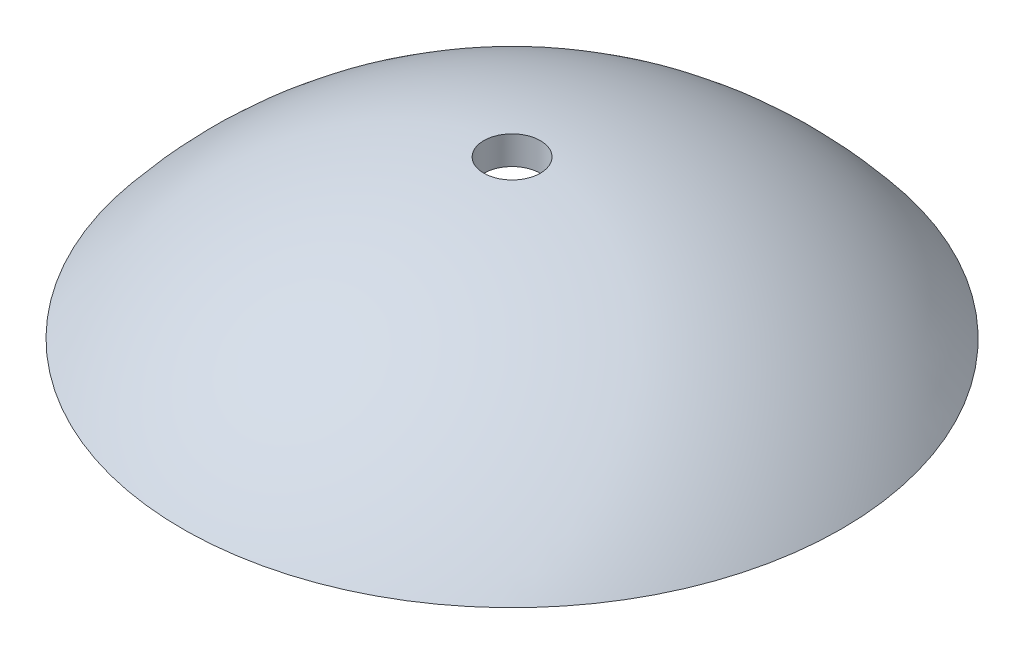
SolidWorks part; units mm, degrees
ref_plane "Front Plane" through (0, 0, 0) normal (0, 0, 1) x (1, 0, 0)
ref_plane "Top Plane" through (0, 0, 0) normal (0, 1, 0) x (1, 0, 0)
ref_plane "Right Plane" through (0, 0, 0) normal (1, 0, 0) x (0, 0, -1)
sketch "Sketch1" plane through (0, 0, 0) normal (0, 0, 1) x (1, 0, 0)
  line L0 (0, 22.4) -> (0, 0)
  line L1 (0, 0) -> (0, -22.4)
  line L2 (0, 51.7877) -> (0, -60.5028) construction
  arc A0 (0, 22.4) -> (0, -22.4) centre (0, 0) ccw
  dimension "D1" = 22.4
revolve "Revolve1" add sketch "Sketch1" angle 360 about L2
sketch "Sketch3" plane through (0, 0, 0) normal (0, 0, 1) x (1, 0, 0)
  line L0 (-33.5065, 14) -> (-33.5065, -28.9466)
  line L1 (-33.5065, -28.9466) -> (32.397, -28.9466)
  line L2 (32.397, -28.9466) -> (32.397, 14)
  line L3 (32.397, 14) -> (-33.5065, 14)
  dimension "D1" = 14
extrude "Cut-Extrude1" cut sketch "Sketch3" against normal mid plane 50
sketch "Sketch4" plane through (0, 0, 0) normal (0, 0, 1) x (1, 0, 0)
  line L0 (0, 0) -> (0, 20.9)
  line L1 (0, 0) -> (0, -20.9)
  line L2 (0, 39.939) -> (0, -32.064) construction
  arc A0 (0, -20.9) -> (0, 20.9) centre (0, 0) cw
  dimension "D1" = 20.9
revolve "Cut-Revolve1" cut sketch "Sketch4" angle 360 about L2
sketch "Sketch5" plane through (0, 0, 0) normal (0, 1, 0) x (1, 0, 0)
  circle A0 centre (0, 0) radius 1.5
  dimension "D1" = 3
extrude "Cut-Extrude2" cut sketch "Sketch5" against normal mid plane 50
